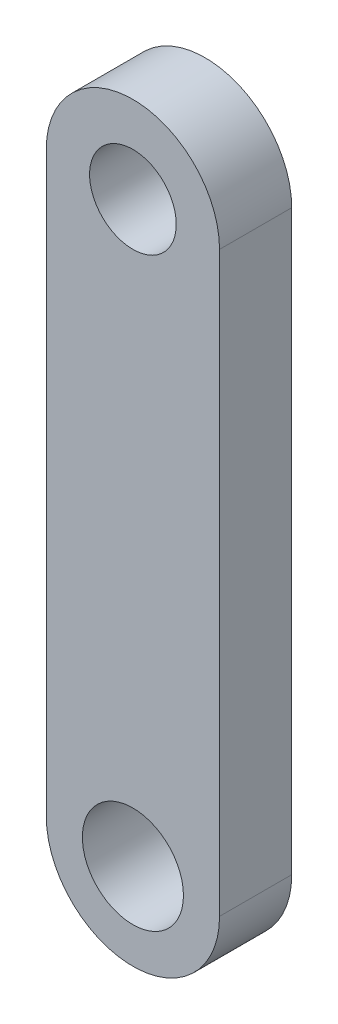
SolidWorks part; units mm, degrees
material "Stop 1060"
ref_plane "Płaszczyzna przednia" through (0, 0, 0) normal (0, 0, 1) x (1, 0, 0)
ref_plane "Płaszczyzna górna" through (0, 0, 0) normal (0, 1, 0) x (1, 0, 0)
ref_plane "Płaszczyzna prawa" through (0, 0, 0) normal (1, 0, 0) x (0, 0, -1)
sketch "Szkic1" plane through (0, 0, 0) normal (0, 0, 1) x (1, 0, 0)
  line L0 (0, 0) -> (0, -40)
  line L1 (-6, -40) -> (-6, 0)
  line L2 (6, -40) -> (6, 0)
  circle A0 centre (0, 0) radius 3
  arc A1 (6, 0) -> (-6, 0) centre (0, 0) ccw
  circle A2 centre (0, -40) radius 3.5
  arc A3 (-6, -40) -> (6, -40) centre (0, -40) ccw
  dimension "D1" = 6
  dimension "D2" = 12
  dimension "7" = 7
  dimension "D5" = 12
  dimension "D3" = 40
extrude "Dodanie-wyciągnięcie1" add sketch "Szkic1" along normal blind 5
